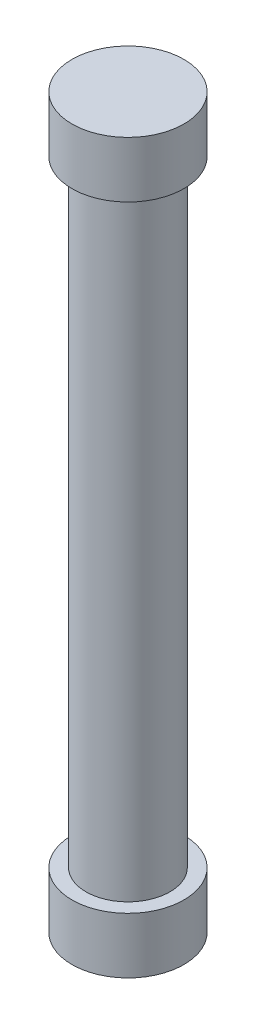
SolidWorks part; units mm, degrees
ref_plane "Front Plane" through (0, 0, 0) normal (0, 0, 1) x (1, 0, 0)
ref_plane "Top Plane" through (0, 0, 0) normal (0, 1, 0) x (1, 0, 0)
ref_plane "Right Plane" through (0, 0, 0) normal (1, 0, 0) x (0, 0, -1)
sketch "Sketch1" plane through (0, 0, 0) normal (0, 0, 1) x (1, 0, 0)
  line L0 (0, 5.0732) -> (0, -20.9268)
  line L1 (0, -20.9268) -> (-2, -20.9268)
  line L2 (-2, -20.9268) -> (-2, -18.9268)
  line L3 (-2, -18.9268) -> (-1.5, -18.9268)
  line L4 (-1.5, -18.9268) -> (-1.5, 3.0732)
  line L5 (-1.5, 3.0732) -> (-2, 3.0732)
  line L6 (-2, 3.0732) -> (-2, 5.0732)
  line L7 (-2, 5.0732) -> (0, 5.0732)
  dimension "D1" = 2
  dimension "D2" = 1.5
  dimension "D3" = 2
  dimension "D4" = 2
  dimension "D5" = 26
  dimension "D6" = 2
revolve "Revolve1" add sketch "Sketch1" angle 360 about L0
